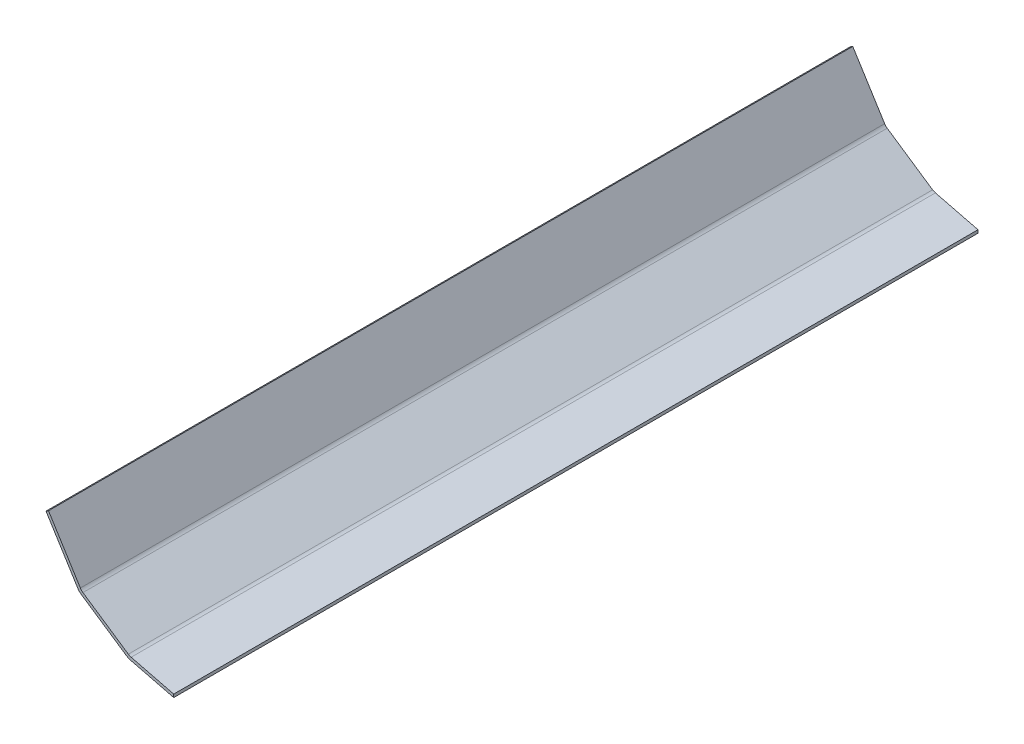
SolidWorks part; units mm, degrees
ref_plane "Front Plane" through (0, 0, 0) normal (0, 0, 1) x (1, 0, 0)
ref_plane "Top Plane" through (0, 0, 0) normal (0, 1, 0) x (1, 0, 0)
ref_plane "Right Plane" through (0, 0, 0) normal (1, 0, 0) x (0, 0, -1)
sketch "Nested support skin behind toe profile" plane through (0, 0, 0) normal (0, 0, 1) x (1, 0, 0)
  line L0 (135.5, 3.0914) -> (121.1003, 6.6816)
  line L1 (120.1484, 7.1054) -> (104.7932, 17.4626)
  line L2 (103.9267, 18.36) -> (93.152, 35.6031)
  line L3 (93.152, 35.6031) -> (92.3039, 35.0732)
  line L4 (92.3039, 35.0732) -> (103.0786, 17.83)
  line L5 (104.234, 16.6336) -> (119.5893, 6.2764)
  line L6 (120.8583, 5.7113) -> (135.5, 2.0607)
  line L7 (135.5, 2.0607) -> (135.5, 3.0914)
  arc A0 (121.1003, 6.6816) -> (120.1484, 7.1054) centre (121.826, 9.5925) cw
  arc A1 (104.7932, 17.4626) -> (103.9267, 18.36) centre (106.4708, 19.9497) cw
  arc A2 (103.0786, 17.83) -> (104.234, 16.6336) centre (106.4708, 19.9497) ccw
  arc A3 (119.5893, 6.2764) -> (120.8583, 5.7113) centre (121.826, 9.5925) ccw
extrude "Nested support skin behind toe" add sketch "Nested support skin behind toe profile" along normal blind 272
